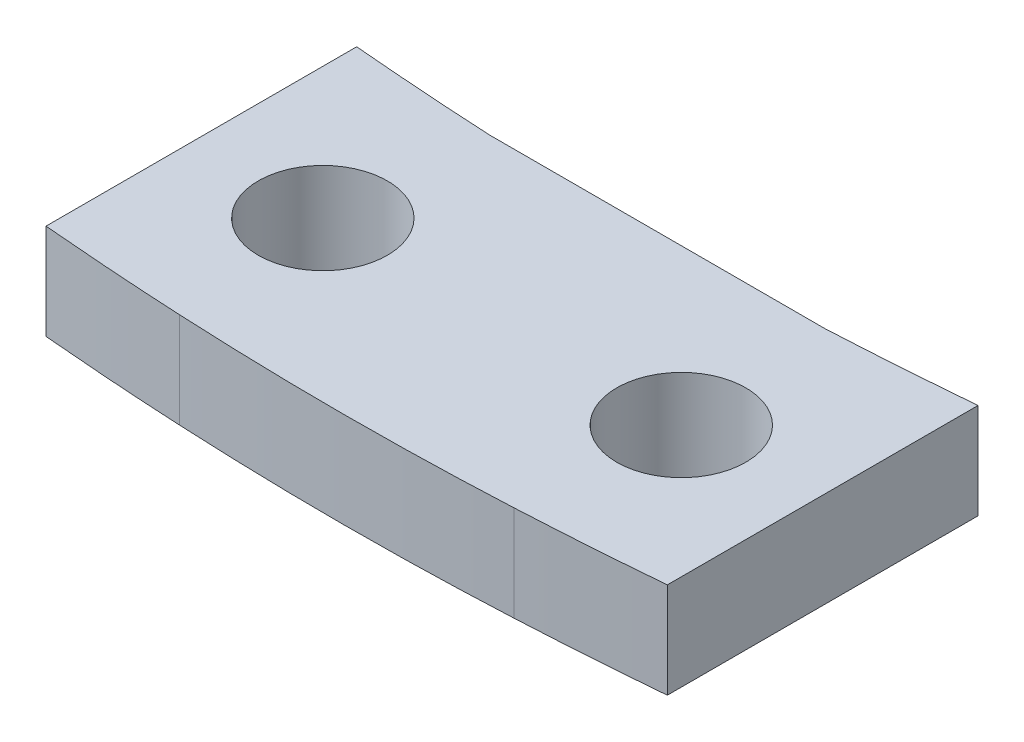
SolidWorks part; units mm, degrees
material "PLA Black"
ref_plane "Front" through (0, 0, 0) normal (0, 0, 1) x (1, 0, 0)
ref_plane "Top" through (0, 0, 0) normal (0, 1, 0) x (1, 0, 0)
ref_plane "Right" through (0, 0, 0) normal (1, 0, 0) x (0, 0, -1)
sketch "Sketch1" plane through (0, 0, 0) normal (0, 1, 0) x (1, 0, 0)
  line L0 (13, 6.9166) -> (13, -6.0834) construction
  line L1 (-13, 6.9166) -> (-13, -6.0834) construction
  line L2 (13, 6.9166) -> (13, -6.0834)
  line L3 (-13, 6.9166) -> (-13, -6.0834)
  line L4 (7, 6.5) -> (-7, 6.5)
  circle A0 centre (-7.5, 0) radius 2.7 construction
  circle A1 centre (7.5, 0) radius 2.7 construction
  circle A2 centre (-7.5, 0) radius 2.7
  circle A3 centre (7.5, 0) radius 2.7
  spline S0 degree 3 poles (259.5451, 957.3219) (178.2672, 59.0746) (-36.3132, -100.5853) (-226.957, 126.42) (49.081, -1004.1512) knots -45.38546 -45.38546 -45.38546 -45.38546 0.56 56.519013 56.519013 56.519013 56.519013 only from (-7, -6.5) to (-13, -6.0834) construction
  spline S1 degree 3 poles (-990.9676, 57.2198) (-264.6411, 17.5727) (67.8465, -3.6753) (5.3504, -6.5775) (3.1788, -6.6521) (1.021, -6.6761) (-0.2785, -6.6761) (-1.579, -6.6721) (-3.7404, -6.635) (-5.6325, -6.5644) (-67.8533, -3.675) (264.6309, 17.5819) (990.9572, 57.2465) knots -13.015641 -13.015641 -13.015641 -13.015641 0.036448 0.036448 0.28 0.5 0.5 0.56 0.78 0.963553 0.963553 14.017217 14.017217 14.017217 14.017217 only from (7, -6.5) to (-7, -6.5) construction
  spline S2 degree 3 poles (109.2667, -1001.4388) (227.2303, 129.4425) (35.9098, -103.8784) (-179.7389, 62.3077) (-162.8901, 978.9595) knots -55.662494 -55.662494 -55.662494 -55.662494 0.56 46.661699 46.661699 46.661699 46.661699 only from (13, -6.0834) to (7, -6.5) construction
  spline S3 degree 3 poles (-7, -6.5) (-8.1213, -6.4441) (-10.1224, -6.3209) (-12.1212, -6.1605) (-13, -6.0834) knots 0 0 0 0 0.56 1 1 1 1
  spline S4 degree 3 poles (7, -6.5) (6.8348, -6.5082) (6.6666, -6.5163) (5.3504, -6.5775) (3.1788, -6.6521) (1.021, -6.6761) (-0.2785, -6.6761) (-1.579, -6.6721) (-3.7404, -6.635) (-5.6325, -6.5644) (-6.6666, -6.5163) (-6.8348, -6.5082) (-7, -6.5) knots 0 0 0 0 0.036448 0.036448 0.28 0.5 0.5 0.56 0.78 0.963553 0.963553 1 1 1 1
  spline S5 degree 3 poles (13, -6.0834) (11.8815, -6.1815) (9.8824, -6.3379) (7.881, -6.4561) (7, -6.5) knots 0 0 0 0 0.56 1 1 1 1
  spline S6 degree 3 poles (-109.2667, -988.4388) (-323.9588, 1069.7501) (200.2866, -1042.5783) (162.8901, 991.9595) knots -12.857931 -12.857931 -12.857931 -12.857931 10.778764 10.778764 10.778764 10.778764 only from (-13, 6.9166) to (-7, 6.5) construction
  spline S7 degree 3 poles (-162.89, 991.9627) (-200.287, -1042.5762) (323.9567, 1069.7421) (109.2681, -988.4255) knots -9.778777 -9.778777 -9.778777 -9.778777 13.85788 13.85788 13.85788 13.85788 only from (7, 6.5) to (13, 6.9166) construction
  spline S8 degree 3 poles (-13, 6.9166) (-11.0026, 6.7413) (-9.0022, 6.5999) (-7, 6.5) knots 0 0 0 0 0.230998 0.230998 0.230998 0.230998
  spline S9 degree 3 poles (7, 6.5) (9.0022, 6.5999) (11.0026, 6.7413) (13, 6.9166) knots 0.769002 0.769002 0.769002 0.769002 1 1 1 1
extrude "Boss-Extrude1" add sketch "Sketch1" along normal blind 4
